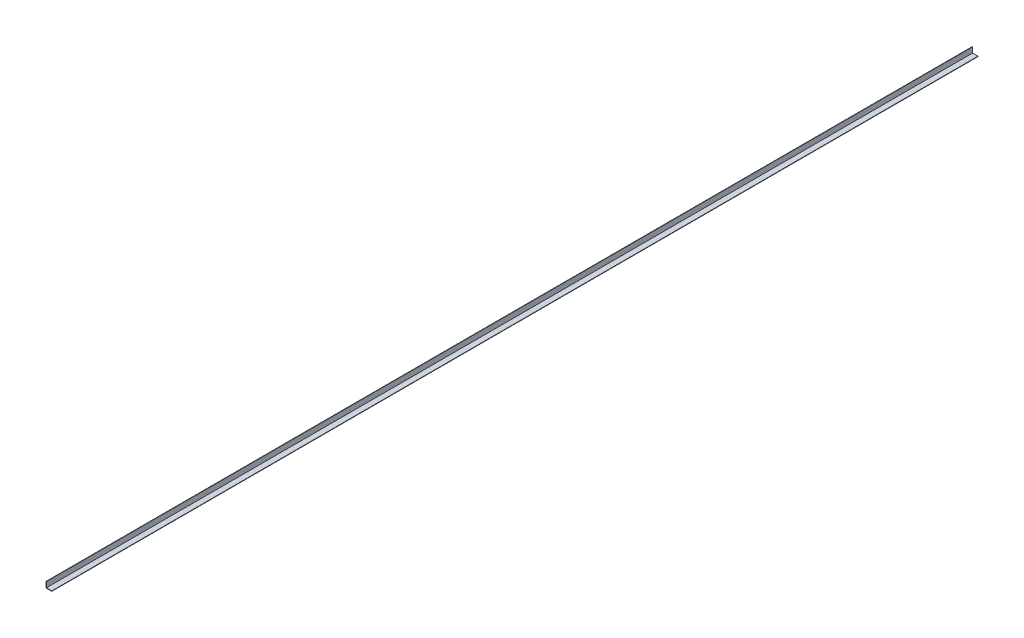
SolidWorks part; units mm, degrees
material "ASTM A36 Acero"
ref_plane "Alzado" through (0, 0, 0) normal (0, 0, 1) x (1, 0, 0)
ref_plane "Planta" through (0, 0, 0) normal (0, 1, 0) x (1, 0, 0)
ref_plane "Vista lateral" through (0, 0, 0) normal (1, 0, 0) x (0, 0, -1)
sketch "Croquis1" plane through (0, 0, 0) normal (0, 0, 1) x (1, 0, 0)
  line L0 (0, 38.1) -> (0, 0)
  line L1 (0, 0) -> (38.1, 0)
  line L2 (38.1, 0) -> (38.1, 2.7)
  line L3 (38.1, 2.7) -> (2.7, 2.7)
  line L4 (2.7, 2.7) -> (2.7, 38.1)
  line L5 (2.7, 38.1) -> (0, 38.1)
  dimension "D1" = 2.7
  dimension "D2" = 38.1
extrude "Saliente-Extruir1" add sketch "Croquis1" against normal blind 6100
